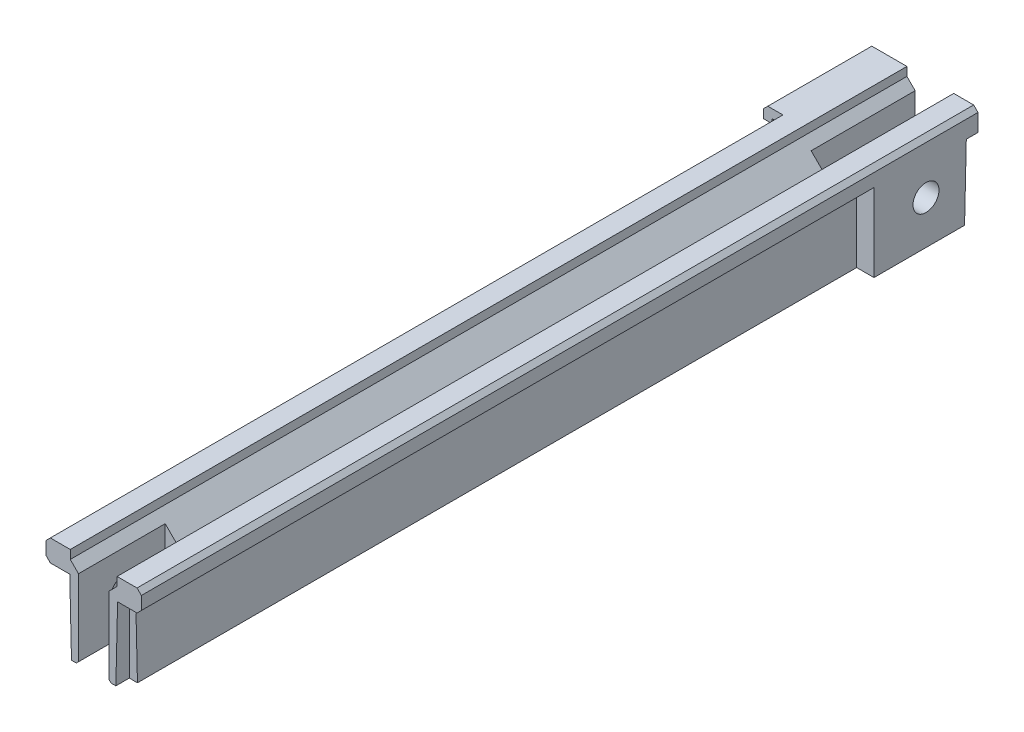
SolidWorks part; units mm, degrees
ref_plane "Front Plane" through (0, 0, 0) normal (0, 0, 1) x (1, 0, 0)
ref_plane "Top Plane" through (0, 0, 0) normal (0, 1, 0) x (1, 0, 0)
ref_plane "Right Plane" through (0, 0, 0) normal (1, 0, 0) x (0, 0, -1)
sketch "Sketch1" plane through (0, 0, 0) normal (0, 0, 1) x (1, 0, 0)
  line L5 (0, 0) -> (5.5, 0)
  line L6 (0, 0) -> (0, 11)
  line L7 (0, 11) -> (5.5, 11)
  line L8 (5.5, 0) -> (5.5, 11)
  dimension "D1" = 11
  dimension "D2" = 5.5
extrude "main_base" add sketch "Sketch1" against normal blind 96.52
sketch "Sketch3" plane through (0, 0, 0) normal (0, 0, 1) x (1, 0, 0)
  line L0 (5.5, 9) -> (3.5, 7)
  line L1 (5.5, 0) -> (5.5, 11) construction
  line L2 (3.5, 7) -> (3.5, 0)
  line L3 (0, 0) -> (5.5, 0) construction
  line L4 (3.5, 0) -> (5.5, 0)
  line L5 (5.5, 0) -> (5.5, 9)
  line L6 (5.5, 11) -> (0, 11) construction
  dimension "D1" = 4
  dimension "D2" = 2
  dimension "D3" = 2
extrude "side_cut_out" cut sketch "Sketch3" against normal offset from surface (84.52 mm away) 12 up to face at (2.75, 5.5, -96.52)
sketch "Sketch4" plane through (0, 0, 0) normal (0, 0, 1) x (1, 0, 0)
  line L1 (5.5, 11) -> (0, 11) construction
  line L2 (0, 11) -> (0, 0) construction
  line L3 (0, 7.3) -> (0, 11)
  line L4 (0, 11) -> (2.7, 11)
  line L5 (2.7, 11) -> (2.7, 10)
  line L6 (2.7, 10) -> (0, 7.3)
  dimension "D1" = 1
  dimension "D2" = 2.7
  dimension "D3" = 45
extrude "top_rubber_band_cut_out" cut sketch "Sketch4" against normal through all
sketch "Sketch5" plane through (0, 0, 0) normal (0, 0, 1) x (1, 0, 0)
  line L0 (2, 0) -> (0, 2)
  line L1 (0, 0) -> (3.5, 0) construction
  line L2 (0, 7.3) -> (0, 0) construction
  line L3 (0, 2) -> (0, 0)
  line L4 (0, 0) -> (2, 0)
  dimension "D1" = 2
  dimension "D2" = 2
extrude "bottom_rubber_band_cut_out" cut sketch "Sketch5" against normal through all
sketch "Sketch6" plane through (0, 0, -96.52) normal (0, 0, -1) x (-1, 0, 0)
  line L0 (-1.75, 0) -> (-1.75, 11)
  line L1 (-2, 0) -> (-5.5, 0) construction
  line L2 (-5.5, 11) -> (-2.7, 11) construction
  line L3 (-1.75, 11) -> (0, 11)
  line L4 (0, 11) -> (0, 0)
  line L5 (0, 0) -> (-1.75, 0)
  dimension "D1" = 1.75
extrude "motor_pulley_cut_out" cut sketch "Sketch6" against normal blind 12
sketch "Sketch7" plane through (0, 0, 0) normal (0, 0, 1) x (1, 0, 0)
  line L0 (5.5, 11) -> (2.7, 11) construction
  line L1 (1.75, 0) -> (0, 0)
  line L2 (1.75, 0) -> (1.75, 11)
  line L3 (1.75, 11) -> (0, 11)
  line L4 (0, 0) -> (0, 11)
  dimension "D1" = 1.75
extrude "pulley_cut_out" cut sketch "Sketch7" against normal blind 10
ref_plane "5mm_mid_plane" through (0, 5, 0) normal (0, 1, 0) x (1, 0, 0)
sketch "Sketch10" plane through (0, 5, 0) normal (0, 1, 0) x (1, 0, 0)
  line L0 (2.75, 5) -> (1.5, 5)
  line L1 (1.5, 5) -> (1.5, 3.75)
  line L3 (1.75, 10) -> (1.75, 0) construction
  line L4 (5.5, 0) -> (2.7, 0) construction
  arc A0 (1.5, 3.75) -> (2.75, 5) centre (1.5, 5) ccw
  dimension "D1" = 1.25
  dimension "D2" = 1.25
  dimension "D3" = 0.25
  dimension "D4" = 5
revolve "half_circle_cut_out" cut sketch "Sketch10" angle 360 about L0
sketch "Sketch11" plane through (1.75, 0, 0) normal (-1, 0, 0) x (0, 0, 1)
  line L1 (-84.52, 11) -> (-96.52, 11) construction
  line L2 (-96.52, 0) -> (-84.52, 0) construction
  circle A0 centre (-90.52, 5) radius 1.5
  point P9 (-90.52, 11)
  dimension "D1" = 3
  dimension "D2" = 5
extrude "motor_shaft_cut_out" cut sketch "Sketch11" against normal through all
sketch "Sketch14" plane through (0, 0, 0) normal (0, 0, 1) x (1, 0, 0)
  line L1 (5.5, 11) -> (7.25, 11)
  line L2 (5.5, 11) -> (5.5, 10)
  line L3 (5.5, 10) -> (7.25, 10)
  line L4 (7.25, 11) -> (7.25, 10)
  dimension "D1" = 1
  dimension "D2" = 1.75
extrude "end_stop" [suppressed] add sketch "Sketch14" against normal blind 5
sketch "Sketch17" plane through (0, 0, 0) normal (0, -1, 0) x (1, 0, 0)
  line L0 (-3.81, 0) -> (3.81, 0) construction
  line L1 (-25.6018, -48.26) -> (27.3161, -48.26) construction
  line L13 (5.5, 0) -> (3.5, 0) construction
  line L22 (5.7, 1.25) -> (2.56, 1.25)
  line L23 (5.7, 1.25) -> (5.7, -1.55)
  line L24 (5.7, -1.55) -> (2.56, -1.55)
  line L25 (2.56, 1.25) -> (2.56, -1.55)
  line L28 (-3.81, -96.52) -> (3.81, -96.52) construction
  line L29 (2.56, -97.77) -> (2.56, -94.97)
  line L30 (5.7, -94.97) -> (2.56, -94.97)
  line L31 (5.7, -97.77) -> (5.7, -94.97)
  line L32 (5.7, -97.77) -> (2.56, -97.77)
  line L33 (5.5, -84.52) -> (5.5, 0) construction
  point P3 (0, 0)
  point P22 (0, -96.52)
  dimension "D1" = 7.62
  dimension "D2" = 2.8
  dimension "D3" = 48.26
  dimension "D4" = 1.25
  dimension "D5" = 1.25
  dimension "D6" = 0.2
extrude "mounting_points" cut sketch "Sketch17" against normal blind 8.5 draft 1.348
mirror "final_mirror" about plane through (0, 0, 0) normal (1, 0, 0) of bodies 120 110
sketch "Sketch13" plane through (0, 0, -96.52) normal (0, 0, -1) x (-1, 0, 0)
  line L1 (5.5, 11) -> (7.25, 11)
  line L2 (5.5, 11) -> (5.5, 10)
  line L3 (5.5, 10) -> (7.25, 10)
  line L4 (7.25, 11) -> (7.25, 10)
  line L5 (7.25, 10) -> (6.25, 10)
  line L6 (7.25, 10) -> (7.25, 9.5)
  line L7 (7.25, 9.5) -> (6.25, 9.5)
  line L8 (6.25, 10) -> (6.25, 9.5)
  line M12 (5.5, 8.4993) -> (5.5, 11)
  dimension "D1" = 1.75
  dimension "D2" = 1
  dimension "D3" = 1
  dimension "D4" = 0.5
extrude "Boss-Extrude3" add sketch "Sketch13" against normal blind 12 contours L4 L1 L3 M12 | L3 L8 L7 L6
chamfer "rail_chamfer" distance 0.5 angle 45 3 edges at (5.5, 11, -48.26) (-5.5, 11, -42.26) (-7.25, 11, -90.52)
fillet "rail_fillet" [suppressed] radius 0.5
